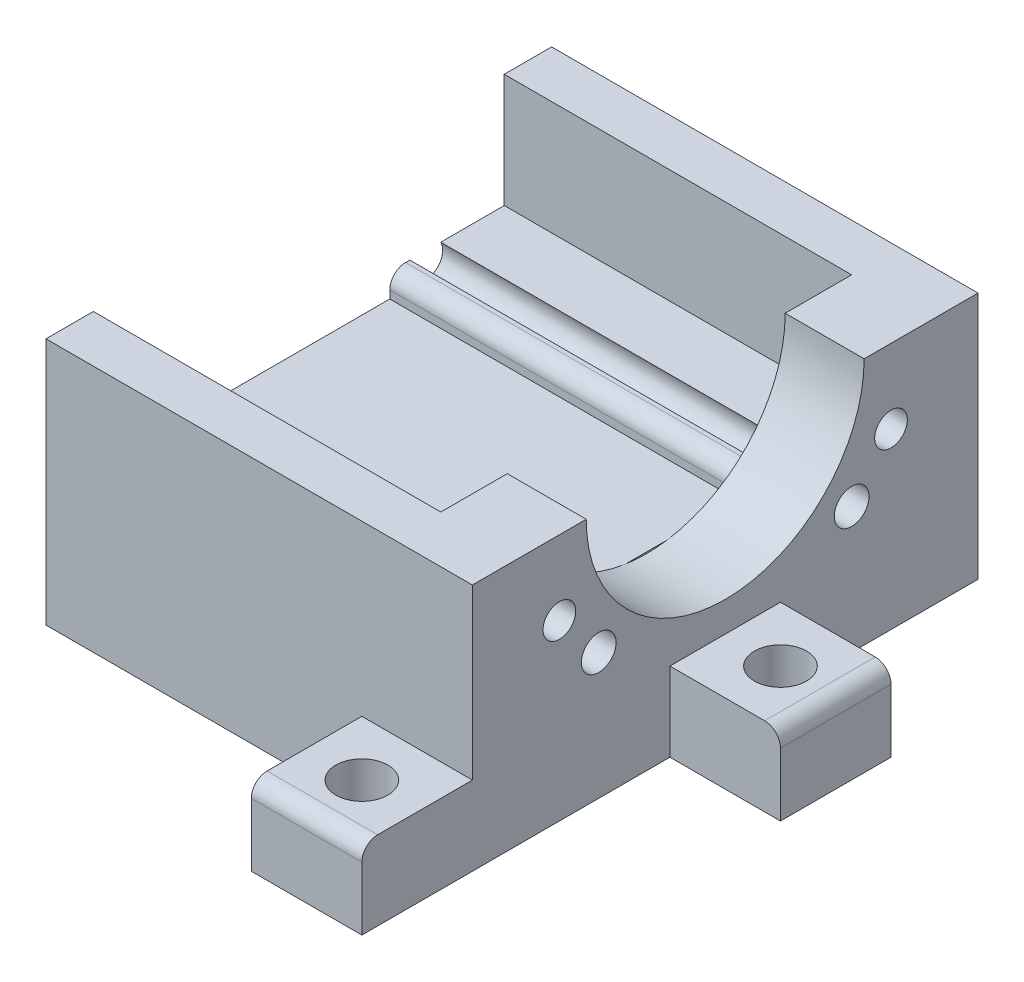
SolidWorks part; units mm, degrees
ref_plane "Front" through (0, 0, 0) normal (0, 0, 1) x (1, 0, 0)
ref_plane "Top" through (0, 0, 0) normal (0, 1, 0) x (1, 0, 0)
ref_plane "Right" through (0, 0, 0) normal (1, 0, 0) x (0, 0, -1)
sketch "Sketch1" plane through (0, 0, 0) normal (1, 0, 0) x (0, 0, -1)
  line L0 (-13.0089, 0) -> (13.0089, 0)
  line L1 (13.0089, 0) -> (13.0089, 8.5)
  line L2 (13.0089, 8.5) -> (5.7589, 8.5)
  line L3 (5.7589, 8.5) -> (5.7589, 7)
  line L4 (5.7589, 7) -> (-5.7589, 7)
  line L5 (-5.7589, 7) -> (-5.7589, 8.5)
  line L6 (-5.7589, 8.5) -> (-13.0089, 8.5)
  line L7 (-13.0089, 8.5) -> (-13.0089, 0)
  dimension "D1" = 8.5
  dimension "D2" = 7.25
  dimension "D3" = 26.0178
  dimension "D4" = 1.5
extrude "Boss-Extrude1" add sketch "Sketch1" along normal mid plane 22
sketch "Sketch3" plane through (0, 0, 0) normal (0, -1, 0) x (1, 0, 0)
  line L1 (-11, -13.0089) -> (11, -13.0089)
  line L2 (-11, -13.0089) -> (-11, -16.0089)
  line L3 (-11, -16.0089) -> (11, -16.0089)
  line L4 (11, -13.0089) -> (11, -16.0089)
  line L5 (-11, 13.0089) -> (11, 13.0089)
  line L6 (-11, 13.0089) -> (-11, 16.0089)
  line L7 (-11, 16.0089) -> (11, 16.0089)
  line L8 (11, 13.0089) -> (11, 16.0089)
  dimension "D1" = 3
  dimension "D2" = 22
  dimension "D3" = 3
  dimension "D4" = 22
extrude "Boss-Extrude2" add sketch "Sketch3" against normal blind 15.7
sketch "Sketch4" plane through (11, 0, 0) normal (1, 0, 0) x (0, 0, -1)
  line L0 (0, 0) -> (0, 15.7) construction
  line L1 (-16.0089, 0) -> (16.0089, 0) construction
  line L2 (-8.8, 15.7) -> (-16.0089, 15.7)
  line L3 (-16.0089, 15.7) -> (-16.0089, 0) construction
  line L4 (-16.0089, 15.7) -> (-16.0089, 0)
  line L5 (-16.0089, 0) -> (16.0089, 0)
  line L6 (16.0089, 0) -> (16.0089, 15.7)
  line L7 (16.0089, 15.7) -> (16.0089, 0) construction
  line L8 (16.0089, 15.7) -> (8.8, 15.7)
  arc A0 (-8.8, 15.7) -> (8.8, 15.7) centre (0, 15.7) ccw
  dimension "D1" = 8.8
  dimension "D2" = 15.7
extrude "Boss-Extrude3" add sketch "Sketch4" along normal blind 5
sketch "Sketch5" plane through (16, 0, 0) normal (1, 0, 0) x (0, 0, -1)
  line L0 (-16.0089, 11) -> (-10.5, 11) construction
  line L1 (-16.0089, 15.7) -> (-16.0089, 0) construction
  line L2 (-10.5, 11) -> (-10.5, 0) construction
  line L3 (-16.0089, 0) -> (16.0089, 0) construction
  line L4 (0, 0) -> (0, 15.7) construction
  line L5 (-16.0089, 8) -> (-8.0089, 8) construction
  line L6 (-8.0089, 8) -> (-8.0089, 0) construction
  circle A0 centre (-10.5, 11) radius 1.035
  circle A1 centre (10.5, 11) radius 1.035
  circle A2 centre (-8.0089, 8) radius 1.1
  circle A3 centre (8.0089, 8) radius 1.1
  dimension "D3" = 2.07
  dimension "D4" = 2.2
  dimension "D1" = 5.5089
  dimension "D2" = 11
  dimension "D5" = 8
  dimension "D6" = 8
extrude "Cut-Extrude1" cut sketch "Sketch5" against normal through all
sketch "Sketch6" plane through (0, 0, 0) normal (0, -1, 0) x (1, 0, 0)
  line L0 (16, 16.0089) -> (16, -16.0089) construction
  line L5 (0, 0) -> (16, 0) construction
  line L13 (16, 3.5) -> (23, 3.5)
  line L15 (16, 16.0089) -> (9, 16.0089)
  line L20 (16, 16.0089) -> (16, 23.0089)
  line L21 (16, 23.0089) -> (9, 23.0089)
  line L22 (9, 16.0089) -> (9, 23.0089)
  line L23 (16, 3.5) -> (16, -3.5)
  line L24 (16, -3.5) -> (23, -3.5)
  line L25 (23, 3.5) -> (23, -3.5)
  point P12 (0, 0)
  dimension "D1" = 7
  dimension "D2" = 7
  dimension "D3" = 7
  dimension "D4" = 7
extrude "Boss-Extrude4" add sketch "Sketch6" against normal blind 5
sketch "Sketch7" plane through (0, 5, 0) normal (0, 1, 0) x (1, 0, 0)
  line L0 (23, 0) -> (16, 0) construction
  line L3 (19.5, 3.5) -> (19.5, -3.5) construction
  line L6 (12.5, -16.0089) -> (12.5, -23.0089) construction
  line L7 (16, -3.5) -> (16, 3.5) construction
  line L8 (23, 3.5) -> (23, -3.5) construction
  line L9 (9, -19.5089) -> (16, -19.5089) construction
  line L10 (16, 3.5) -> (23, 3.5) construction
  line L11 (23, -3.5) -> (16, -3.5) construction
  line L12 (9, -23.0089) -> (9, -16.0089) construction
  line L13 (9, -16.0089) -> (16, -16.0089) construction
  line L14 (16, -23.0089) -> (9, -23.0089) construction
  line L15 (16, -16.0089) -> (16, -23.0089) construction
  circle A0 centre (19.5, 0) radius 1.65
  circle A1 centre (12.5, -19.5089) radius 1.65
  point P2 (0, 0)
  point P5 (16, 0)
  point P8 (0, 0)
  point P11 (23, 0)
  point P14 (0, 0)
  point P29 (19.5, 3.5)
  point P32 (19.5, -3.5)
  dimension "D1" = 3.3
extrude "Cut-Extrude2" cut sketch "Sketch7" against normal through all
fillet "Fillet1" radius 1 4 edges at (12.5, 5, 23.0089) (0, 8.5, 5.7589) (0, 8.5, -5.7589) (23, 5, 0)
